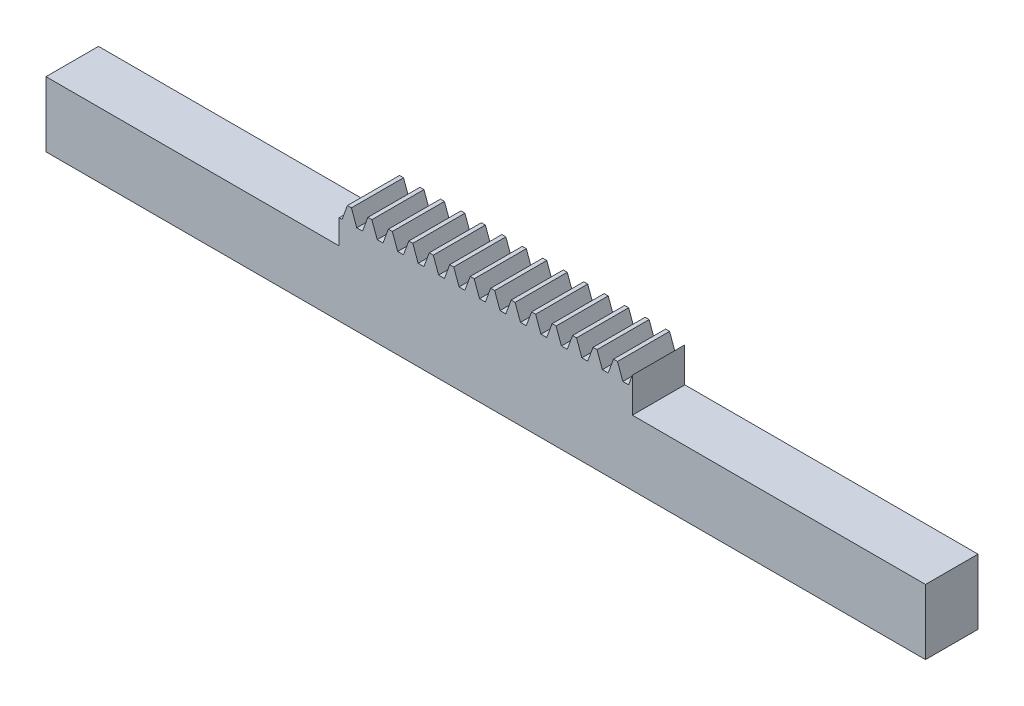
SolidWorks part; units mm, degrees
ref_plane "Front Plane" through (0, 0, 0) normal (0, 0, 1) x (1, 0, 0)
ref_plane "Top Plane" through (0, 0, 0) normal (0, 1, 0) x (1, 0, 0)
ref_plane "Right Plane" through (0, 0, 0) normal (1, 0, 0) x (0, 0, -1)
ref_plane "Plane1" through (0, 0, -3.7928) normal (0, 0, -1) x (-1, 0, 0)
sketch "Sketch1" plane through (0, 0, -3.7928) normal (0, 0, -1) x (-1, 0, 0)
  line L0 (23.517, -6.4086) -> (22.698, -8.6586)
  line L1 (22.698, -8.6586) -> (21.8092, -8.6586)
  line L2 (21.8092, -8.6586) -> (21.2359, -7.0836)
  line L3 (21.2359, -7.0836) -> (21.2359, -12.4086)
  line L4 (21.2359, -12.4086) -> (66.2359, -12.4086)
  line L5 (66.2359, -12.4086) -> (66.2359, -8.6586)
  line L6 (66.2359, -8.6586) -> (65.7915, -8.6586)
  line L7 (65.7915, -8.6586) -> (64.9725, -6.4086)
  line L8 (64.9725, -6.4086) -> (64.3577, -6.4086)
  line L9 (64.3577, -6.4086) -> (63.5387, -8.6586)
  line L10 (63.5387, -8.6586) -> (62.6499, -8.6586)
  line L11 (62.6499, -8.6586) -> (61.8309, -6.4086)
  line L12 (61.8309, -6.4086) -> (61.2161, -6.4086)
  line L13 (61.2161, -6.4086) -> (60.3971, -8.6586)
  line L14 (60.3971, -8.6586) -> (59.5083, -8.6586)
  line L15 (59.5083, -8.6586) -> (58.6893, -6.4086)
  line L16 (58.6893, -6.4086) -> (58.0745, -6.4086)
  line L17 (58.0745, -6.4086) -> (57.2555, -8.6586)
  line L18 (57.2555, -8.6586) -> (56.3667, -8.6586)
  line L19 (56.3667, -8.6586) -> (55.5477, -6.4086)
  line L20 (55.5477, -6.4086) -> (54.9329, -6.4086)
  line L21 (54.9329, -6.4086) -> (54.114, -8.6586)
  line L22 (54.114, -8.6586) -> (53.2251, -8.6586)
  line L23 (53.2251, -8.6586) -> (52.4062, -6.4086)
  line L24 (52.4062, -6.4086) -> (51.7913, -6.4086)
  line L25 (51.7913, -6.4086) -> (50.9724, -8.6586)
  line L26 (50.9724, -8.6586) -> (50.0835, -8.6586)
  line L27 (50.0835, -8.6586) -> (49.2646, -6.4086)
  line L28 (49.2646, -6.4086) -> (48.6497, -6.4086)
  line L29 (48.6497, -6.4086) -> (47.8308, -8.6586)
  line L30 (47.8308, -8.6586) -> (46.9419, -8.6586)
  line L31 (46.9419, -8.6586) -> (46.123, -6.4086)
  line L32 (46.123, -6.4086) -> (45.5081, -6.4086)
  line L33 (45.5081, -6.4086) -> (44.6892, -8.6586)
  line L34 (44.6892, -8.6586) -> (43.8003, -8.6586)
  line L35 (43.8003, -8.6586) -> (42.9814, -6.4086)
  line L36 (42.9814, -6.4086) -> (42.3665, -6.4086)
  line L37 (42.3665, -6.4086) -> (41.5476, -8.6586)
  line L38 (41.5476, -8.6586) -> (40.6587, -8.6586)
  line L39 (40.6587, -8.6586) -> (39.8398, -6.4086)
  line L40 (39.8398, -6.4086) -> (39.2249, -6.4086)
  line L41 (39.2249, -6.4086) -> (38.406, -8.6586)
  line L42 (38.406, -8.6586) -> (37.5171, -8.6586)
  line L43 (37.5171, -8.6586) -> (36.6982, -6.4086)
  line L44 (36.6982, -6.4086) -> (36.0833, -6.4086)
  line L45 (36.0833, -6.4086) -> (35.2644, -8.6586)
  line L46 (35.2644, -8.6586) -> (34.3755, -8.6586)
  line L47 (34.3755, -8.6586) -> (33.5566, -6.4086)
  line L48 (33.5566, -6.4086) -> (32.9417, -6.4086)
  line L49 (32.9417, -6.4086) -> (32.1228, -8.6586)
  line L50 (32.1228, -8.6586) -> (31.2339, -8.6586)
  line L51 (31.2339, -8.6586) -> (30.415, -6.4086)
  line L52 (30.415, -6.4086) -> (29.8001, -6.4086)
  line L53 (29.8001, -6.4086) -> (28.9812, -8.6586)
  line L54 (28.9812, -8.6586) -> (28.0923, -8.6586)
  line L55 (28.0923, -8.6586) -> (27.2734, -6.4086)
  line L56 (27.2734, -6.4086) -> (26.6586, -6.4086)
  line L57 (26.6586, -6.4086) -> (25.8396, -8.6586)
  line L58 (25.8396, -8.6586) -> (24.9508, -8.6586)
  line L59 (24.9508, -8.6586) -> (24.1318, -6.4086)
  line L60 (24.1318, -6.4086) -> (23.517, -6.4086)
extrude "Boss-Extrude1" add sketch "Sketch1" against normal blind 8
sketch "Sketch2" plane through (0, -12.4086, 0) normal (0, -1, 0) x (1, 0, 0)
  line L1 (-111.2359, 4.2072) -> (23.7641, 4.2072)
  line L2 (-111.2359, 4.2072) -> (-111.2359, -3.849)
  line L3 (-111.2359, -3.849) -> (23.7641, -3.849)
  line L4 (23.7641, 4.2072) -> (23.7641, -3.849)
  line L6 (-21.2359, 4.2072) -> (-66.2359, 4.2072) construction
  point P4 (-43.7359, 4.2072)
  dimension "D1" = 8.0562
  dimension "D2" = 135
extrude "Boss-Extrude2" add sketch "Sketch2" along normal blind 10
